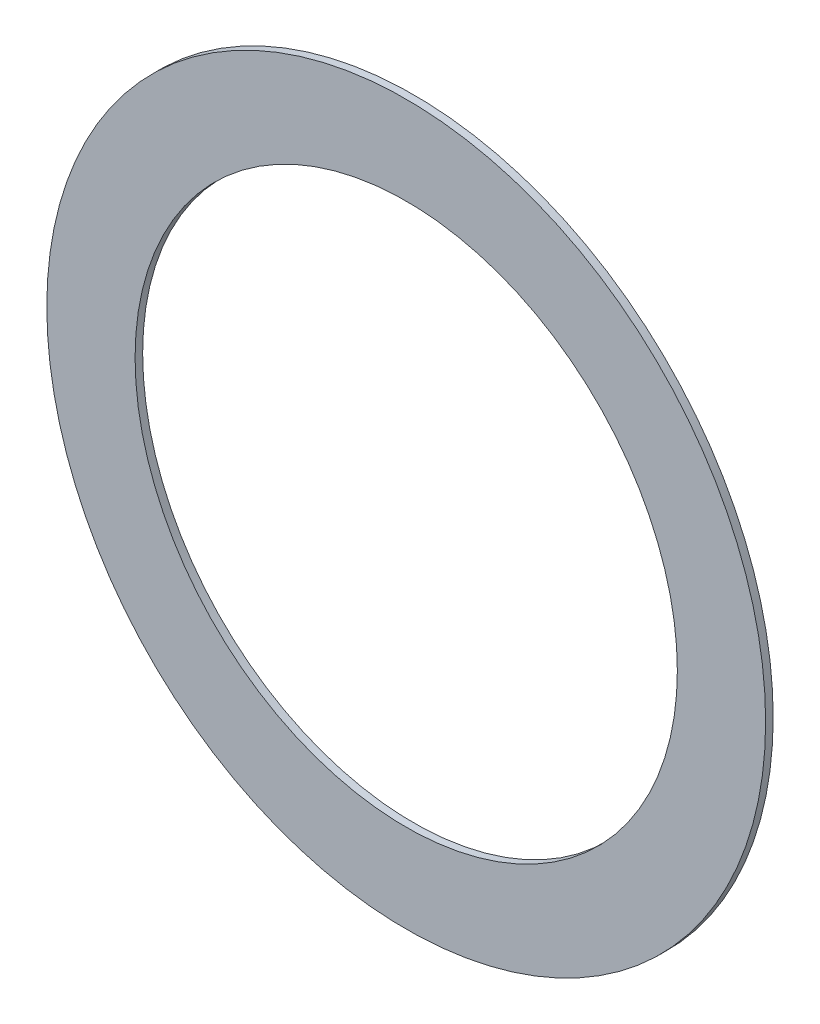
SolidWorks part; units mm, degrees
ref_plane "前基準面" through (0, 0, 0) normal (0, 0, 1) x (1, 0, 0)
ref_plane "上基準面" through (0, 0, 0) normal (0, 1, 0) x (1, 0, 0)
ref_plane "右基準面" through (0, 0, 0) normal (1, 0, 0) x (0, 0, -1)
sketch "草圖1" plane through (0, 0, 0) normal (0, 0, 1) x (1, 0, 0)
  circle A0 centre (0, 0) radius 28.5
  circle A1 centre (0, 0) radius 21.5
  dimension "D1" = 7
  dimension "D2" = 43
extrude "填料-伸長1" add sketch "草圖1" along normal blind 0.6
